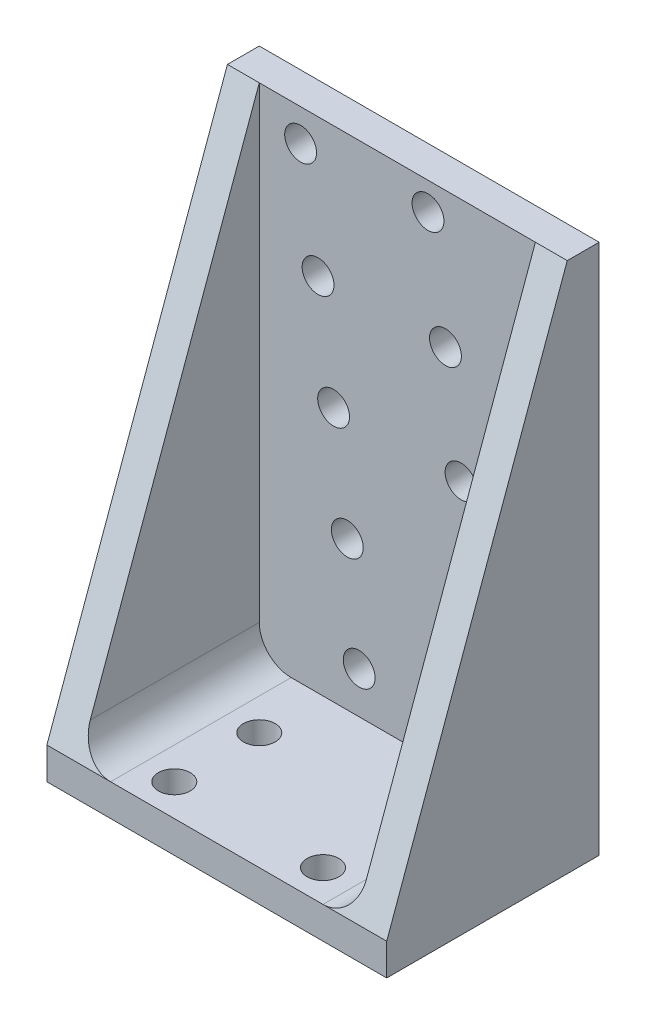
SolidWorks part; units mm, degrees
material "6061-T6 (SS)"
ref_plane "前视基准面" through (0, 0, 0) normal (0, 0, 1) x (1, 0, 0)
ref_plane "上视基准面" through (0, 0, 0) normal (0, 1, 0) x (1, 0, 0)
ref_plane "右视基准面" through (0, 0, 0) normal (1, 0, 0) x (0, 0, -1)
sketch "草图1" plane through (0, 0, 0) normal (0, 0, 1) x (1, 0, 0)
  line L0 (-580, 0) -> (0, 0) construction
  line L1 (0, 365.6501) -> (0, -284.4096) construction
  line L2 (-580, 0) -> (-580, -79) construction
  line L3 (-580, -79) -> (0, 0) construction
  line L4 (-580, -79) -> (-6, 0) construction
  line L5 (-16, 23) -> (16, 23)
  line L6 (-16, 23) -> (-16, -27)
  line L7 (-16, -27) -> (16, -27)
  line L8 (16, 23) -> (16, -27)
  line L9 (-16, 23) -> (16, -27) construction
  line L10 (-16, -27) -> (16, 23) construction
  line L11 (-580, -79) -> (-4.7087, -10.0297) construction
  line L12 (-580, -79) -> (-6, 0) construction
  line L13 (-580, -79) -> (-7.4662, 10.0056) construction
  circle A0 centre (-6, 0) radius 1.5
  circle A1 centre (6, 0) radius 1.5
  circle A10 centre (-4.7087, -10.0297) radius 1.5
  circle A11 centre (7.2895, -10.2391) radius 1.5
  circle A12 centre (-3.5926, -20.0804) radius 1.5
  circle A13 centre (8.4001, -20.4992) radius 1.5
  circle A14 centre (-7.4662, 10.0056) radius 1.5
  circle A15 centre (4.532, 10.2151) radius 1.5
  circle A16 centre (-9.1067, 19.9842) radius 1.5
  circle A17 centre (2.886, 20.403) radius 1.5
  point P11 (-8.5116, 20.4865)
  point P12 (0, 0)
  point P31 (0, -2)
  dimension "D4" = 3
  dimension "D6" = 1
  dimension "D1" = 580
  dimension "D2" = 79
  dimension "D3" = 3
  dimension "D5" = 12
  dimension "D7" = 32
  dimension "D8" = 27
  dimension "D9" = 50
  dimension "D10" = 579.4109
  dimension "D12" = 1
  dimension "D13" = 579.4109
  dimension "D11" = 3
extrude "凸台-拉伸1" add sketch "草图1" along normal blind 3
sketch "草图2" plane through (0, -27, 0) normal (0, -1, 0) x (1, 0, 0)
  line L0 (0, -7.679) -> (0, 31.2636) construction
  line L2 (-16, 20) -> (16, 20)
  line L3 (-16, 20) -> (-16, 0)
  line L4 (-16, 0) -> (16, 0)
  line L5 (16, 20) -> (16, 0)
  line L6 (-16, 20) -> (16, 0) construction
  line L7 (-16, 0) -> (16, 20) construction
  circle A0 centre (7, 9) radius 1.5
  circle A1 centre (7, 17) radius 1.5
  circle A2 centre (-7, 17) radius 1.5
  circle A3 centre (-7, 9) radius 1.5
  point P3 (0, 10)
  dimension "D2" = 3
  dimension "D1" = 20
  dimension "D3" = 14
  dimension "D4" = 3
  dimension "D5" = 8
extrude "凸台-拉伸2" add sketch "草图2" against normal blind 3
sketch "草图3" plane through (16, 0, 0) normal (1, 0, 0) x (0, 0, -1)
  line L0 (-3, 23) -> (-20, -24)
rib "筋2" sketch "草图3" sketch "草图3" thickness 3 extrusion direction parallel to sketch draft on no parameters "D1"=3
mirror "镜向1" about plane through (0, 0, 0) normal (1, 0, 0) of "筋2"
fillet "圆角1" radius 3 2 edges at (13, -24, 11.5) (-13, -24, 11.5)
